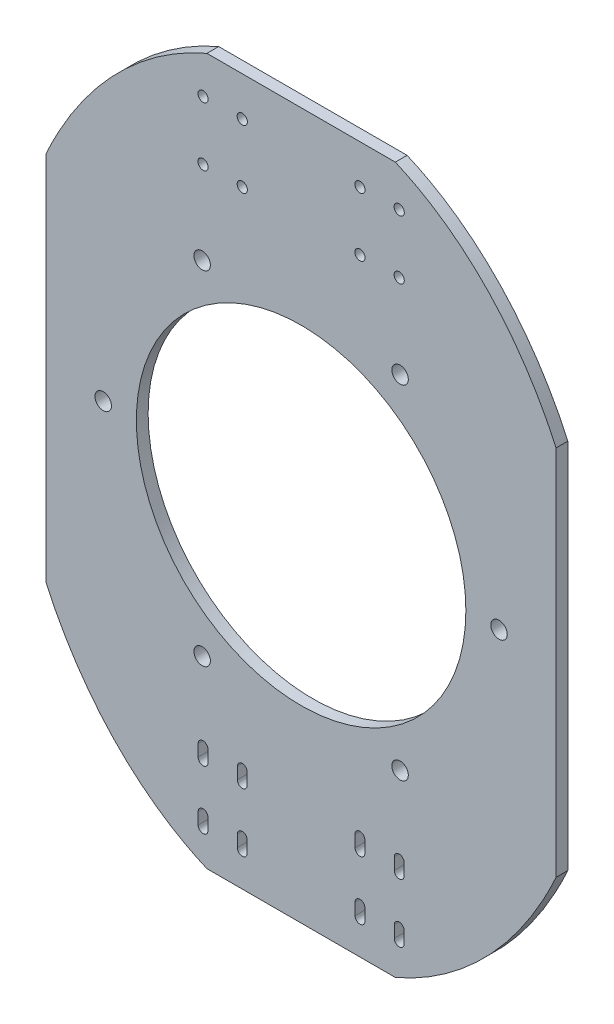
SolidWorks part; units mm, degrees
material "Thornel Mat VMA"
ref_plane "Front" through (0, 0, 0) normal (0, 0, 1) x (1, 0, 0)
ref_plane "Top" through (0, 0, 0) normal (0, 1, 0) x (1, 0, 0)
ref_plane "Right" through (0, 0, 0) normal (1, 0, 0) x (0, 0, -1)
sketch "草图1" plane through (0, 0, 0) normal (0, 0, 1) x (1, 0, 0)
  line L1 (-65, -90) -> (65, -90)
  line L2 (-65, -90) -> (-65, 90)
  line L3 (-65, 90) -> (65, 90)
  line L4 (65, -90) -> (65, 90)
  line L5 (-65, -90) -> (65, 90) construction
  line L6 (-65, 90) -> (65, -90) construction
  point P0 (0, 0)
  dimension "D1" = 130
  dimension "D2" = 180
extrude "凸台-拉伸1" add sketch "草图1" along normal blind 3
sketch "草图2" plane through (0, 0, 0) normal (0, 0, -1) x (-1, 0, 0)
  line L0 (-65, 0) -> (65, 0) construction
  line L1 (-65, -90) -> (-65, 90) construction
  line L2 (65, 90) -> (65, -90) construction
  line L3 (65, -90) -> (-65, -90) construction
  circle A2 centre (55, -80) radius 2.5
  circle A3 centre (-55, -80) radius 2.5
  circle A6 centre (55, 80) radius 2.5
  circle A7 centre (-55, 80) radius 2.5
  dimension "D4" = 5
  dimension "D5" = 10
  dimension "D6" = 10
  dimension "D7" = 5
  dimension "D8" = 10
  dimension "D9" = 10
sketch "草图3" plane through (0, 0, 3) normal (0, 0, 1) x (1, 0, 0)
  line L1 (65, -90) -> (65, 90) construction
  circle A0 centre (55, 30) radius 1.5
  circle A1 centre (55, -30) radius 1.5
  dimension "D1" = 3
  dimension "D2" = 10
  dimension "D3" = 30
  dimension "D4" = 3
  dimension "D5" = 30
  dimension "D6" = 10
sketch "草图4" plane through (0, 0, 3) normal (0, 0, 1) x (1, 0, 0)
  line L0 (65, 0) -> (0, 0) construction
  line L4 (-65, 90) -> (-65, -90) construction
  line L5 (-25, -63.5) -> (-25, -66.5) construction
  line L6 (-23.75, -63.5) -> (-23.75, -66.5)
  line L7 (-26.25, -63.5) -> (-26.25, -66.5)
  line L8 (-15, -63.5) -> (-15, -66.5) construction
  line L9 (-13.75, -63.5) -> (-13.75, -66.5)
  line L10 (-16.25, -63.5) -> (-16.25, -66.5)
  line L11 (-25, -78.5) -> (-25, -81.5) construction
  line L12 (-23.75, -78.5) -> (-23.75, -81.5)
  line L13 (-26.25, -78.5) -> (-26.25, -81.5)
  line L14 (-15, -78.5) -> (-15, -81.5) construction
  line L15 (-13.75, -78.5) -> (-13.75, -81.5)
  line L16 (-16.25, -78.5) -> (-16.25, -81.5)
  line L17 (0, 0) -> (0, -29.7952) construction
  line L18 (-65, -90) -> (65, -90) construction
  line L19 (15, -78.5) -> (15, -81.5) construction
  line L20 (13.75, -78.5) -> (13.75, -81.5)
  line L21 (16.25, -78.5) -> (16.25, -81.5)
  line L22 (25, -78.5) -> (25, -81.5) construction
  line L23 (23.75, -78.5) -> (23.75, -81.5)
  line L24 (26.25, -78.5) -> (26.25, -81.5)
  line L25 (25, -63.5) -> (25, -66.5) construction
  line L26 (23.75, -63.5) -> (23.75, -66.5)
  line L27 (26.25, -63.5) -> (26.25, -66.5)
  line L28 (15, -63.5) -> (15, -66.5) construction
  line L29 (13.75, -63.5) -> (13.75, -66.5)
  line L30 (16.25, -63.5) -> (16.25, -66.5)
  circle A0 centre (15, 65) radius 1.3
  circle A1 centre (25, 65) radius 1.3
  circle A2 centre (25, 80) radius 1.3
  circle A3 centre (15, 80) radius 1.3
  circle A4 centre (-25, 80) radius 1.3
  circle A5 centre (-15, 80) radius 1.3
  circle A6 centre (-15, 65) radius 1.3
  circle A7 centre (-25, 65) radius 1.3
  arc A16 (-23.75, -63.5) -> (-26.25, -63.5) centre (-25, -63.5) ccw
  arc A17 (-26.25, -66.5) -> (-23.75, -66.5) centre (-25, -66.5) ccw
  arc A18 (-13.75, -63.5) -> (-16.25, -63.5) centre (-15, -63.5) ccw
  arc A19 (-16.25, -66.5) -> (-13.75, -66.5) centre (-15, -66.5) ccw
  arc A20 (-23.75, -78.5) -> (-26.25, -78.5) centre (-25, -78.5) ccw
  arc A21 (-26.25, -81.5) -> (-23.75, -81.5) centre (-25, -81.5) ccw
  arc A22 (-13.75, -78.5) -> (-16.25, -78.5) centre (-15, -78.5) ccw
  arc A23 (-16.25, -81.5) -> (-13.75, -81.5) centre (-15, -81.5) ccw
  arc A24 (13.75, -78.5) -> (16.25, -78.5) centre (15, -78.5) cw
  arc A25 (16.25, -81.5) -> (13.75, -81.5) centre (15, -81.5) cw
  arc A26 (23.75, -78.5) -> (26.25, -78.5) centre (25, -78.5) cw
  arc A27 (26.25, -81.5) -> (23.75, -81.5) centre (25, -81.5) cw
  arc A28 (23.75, -63.5) -> (26.25, -63.5) centre (25, -63.5) cw
  arc A29 (26.25, -66.5) -> (23.75, -66.5) centre (25, -66.5) cw
  arc A30 (13.75, -63.5) -> (16.25, -63.5) centre (15, -63.5) cw
  arc A31 (16.25, -66.5) -> (13.75, -66.5) centre (15, -66.5) cw
  point P24 (-15, -80)
  point P34 (15, -80)
  point P41 (25, -80)
  point P44 (-25, -65)
  point P51 (-15, -65)
  point P58 (-25, -80)
  point P65 (-15, -80)
  point P75 (25, -65)
  point P82 (15, -65)
  dimension "D1" = 2.6
  dimension "D9" = 3
  dimension "D10" = 2.5
  dimension "D6" = 30
  dimension "D7" = 10
  dimension "D8" = 130
  dimension "D11" = 10
  dimension "D12" = 15
  dimension "D13" = 10
  dimension "D14" = 40
  dimension "D15" = 15
  dimension "D16" = 10
  dimension "D2" = 2
  dimension "D3" = 2
  dimension "D4" = 2
  dimension "D5" = 2
sketch "草图5" plane through (0, 0, 3) normal (0, 0, 1) x (1, 0, 0)
  circle A0 centre (0, 0) radius 42
  dimension "D1" = 84
extrude "切除-拉伸2" cut sketch "草图5" against normal blind 10
sketch "草图8" plane through (0, 0, 3) normal (0, 0, 1) x (1, 0, 0)
  line L0 (65, 0) -> (-65, 0) construction
  circle A0 centre (0, 0) radius 50.45 construction
  circle A1 centre (-50.45, 0) radius 2.1
  circle A2 centre (-25.225, 43.691) radius 2.1
  circle A3 centre (25.225, 43.691) radius 2.1
  circle A4 centre (50.45, 0) radius 2.1
  circle A5 centre (25.225, -43.691) radius 2.1
  circle A6 centre (-25.225, -43.691) radius 2.1
  point P23 (0, 0)
  dimension "D1" = 4.2
  dimension "D3" = 100.9
  dimension "D2" = 6
extrude "切除-拉伸5" cut sketch "草图8" against normal blind 10
sketch "草图9" plane through (0, 0, 3) normal (0, 0, 1) x (1, 0, 0)
  line L5 (65, 0) -> (-65, 0) construction
  ellipse E0 centre (0, 0) end of major axis (0, -95) minor radius 75
  dimension "D1" = 75
  dimension "D2" = 95
extrude "切除-拉伸7" cut sketch "草图9" against normal blind 10 flip side to cut
extrude "切除-拉伸8" cut sketch "草图4" against normal up to next
